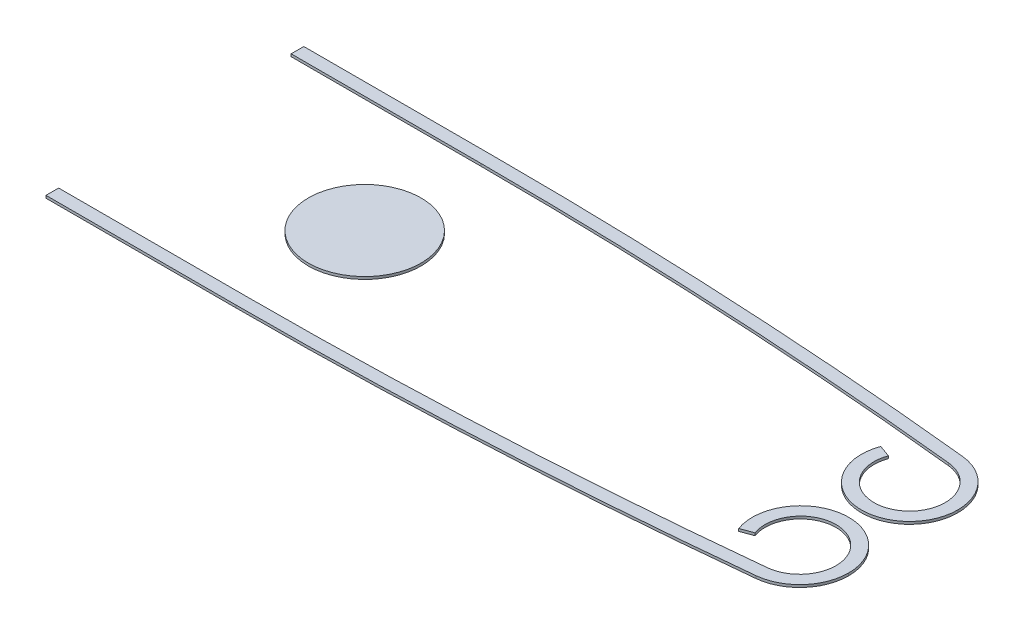
SolidWorks part; units mm, degrees
ref_plane "Front Plane" through (0, 0, 0) normal (0, 0, 1) x (1, 0, 0)
ref_plane "Top Plane" through (0, 0, 0) normal (0, 1, 0) x (1, 0, 0)
ref_plane "Right Plane" through (0, 0, 0) normal (1, 0, 0) x (0, 0, -1)
sketch "Sketch1" plane through (0, 0, 0) normal (0, 1, 0) x (1, 0, 0)
  line L0 (0, 50.9319) -> (-75, 50.9319)
  line L1 (0, 0) -> (224.4913, 0) construction
  line L2 (0, 45.9319) -> (-75, 45.9319)
  line L3 (-75, 50.9319) -> (-75, 45.9319)
  line L4 (180.5471, 26.3547) -> (175.8485, 28.0646)
  line L5 (180.5471, -26.3547) -> (175.8485, -28.0646)
  line L6 (-75, -50.9319) -> (-75, -45.9319)
  line L7 (0, -45.9319) -> (-75, -45.9319)
  line L8 (0, -50.9319) -> (-75, -50.9319)
  circle A0 centre (0, 0) radius 22.3
  arc A1 (0, 50.9319) -> (195.443, 40.8042) centre (0, -1839.9431) cw
  arc A2 (195.443, 40.8042) -> (212.8, 21.55) centre (193.4422, 21.55) cw
  arc A3 (212.8, 21.55) -> (175.8485, 28.0646) centre (193.75, 21.55) cw
  arc A4 (207.8, 21.55) -> (180.5471, 26.3547) centre (193.75, 21.55) cw
  arc A5 (194.9262, 35.8309) -> (207.8, 21.55) centre (193.4422, 21.55) cw
  arc A6 (0, 45.9319) -> (194.9262, 35.8309) centre (0, -1839.9431) cw
  arc A7 (212.8, -21.55) -> (175.8485, -28.0646) centre (193.75, -21.55) ccw
  arc A8 (207.8, -21.55) -> (180.5471, -26.3547) centre (193.75, -21.55) ccw
  arc A9 (194.9262, -35.8309) -> (207.8, -21.55) centre (193.4422, -21.55) ccw
  arc A10 (195.443, -40.8042) -> (212.8, -21.55) centre (193.4422, -21.55) ccw
  arc A11 (0, -45.9319) -> (194.9262, -35.8309) centre (0, 1839.9431) ccw
  arc A12 (0, -50.9319) -> (195.443, -40.8042) centre (0, 1839.9431) ccw
  point P13 (174.7, 21.55)
  point P14 (22.3, 0)
  point P15 (193.75, 2.5)
  point P17 (0, 22.3)
  point P19 (212.8, 21.55)
  dimension "D1" = 44.6
  dimension "D5" = 19.05
  dimension "D2" = 5
  dimension "D3" = 75
  dimension "D4" = 152.4
  dimension "D6" = 5
extrude "Boss-Extrude1" add sketch "Sketch1" along normal mid plane 1
